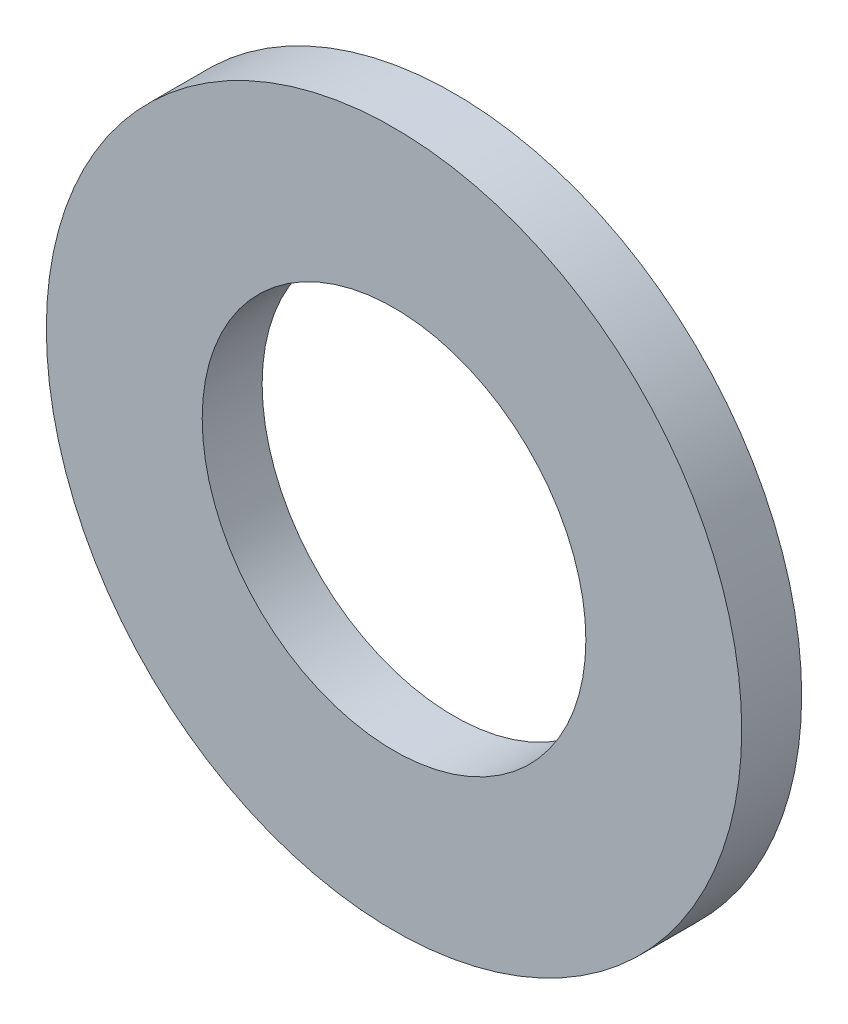
SolidWorks part; units mm, degrees
material "AISI 4340 Steel, normalized"
ref_plane "Front Plane" through (0, 0, 0) normal (0, 0, 1) x (1, 0, 0)
ref_plane "Top Plane" through (0, 0, 0) normal (0, 1, 0) x (1, 0, 0)
ref_plane "Right Plane" through (0, 0, 0) normal (1, 0, 0) x (0, 0, -1)
sketch "Sketch1" plane through (0, 0, 0) normal (0, 0, 1) x (1, 0, 0)
  circle A0 centre (0, 0) radius 3.5
  circle A1 centre (0, 0) radius 1.6
extrude "Washer_Envelope" add sketch "Sketch1" along normal blind 0.5
sketch "Sketch2" plane through (0, 0, 0) normal (0, 0, 1) x (1, 0, 0)
  circle A0 centre (0, 0) radius 2.9
  circle A1 centre (0, 0) radius 3.8
extrude "Bench_DIN433_OD5p8_Trim" cut sketch "Sketch2" against normal through all and the other way through all
